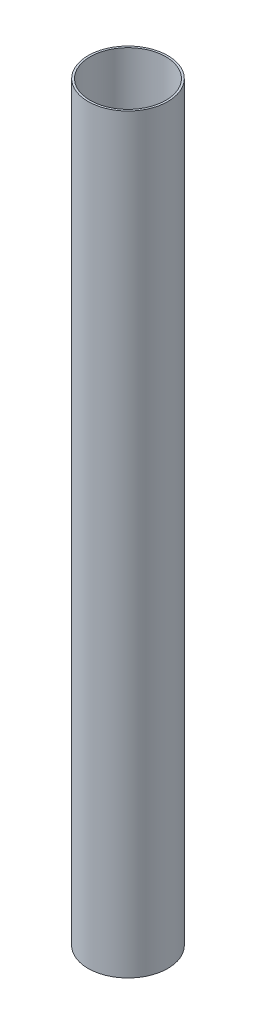
SolidWorks part; units mm, degrees
ref_plane "Front Plane" through (0, 0, 0) normal (0, 0, 1) x (1, 0, 0)
ref_plane "Top Plane" through (0, 0, 0) normal (0, 1, 0) x (1, 0, 0)
ref_plane "Right Plane" through (0, 0, 0) normal (1, 0, 0) x (0, 0, -1)
sketch "Sketch1" plane through (0, 0, 0) normal (0, 1, 0) x (1, 0, 0)
  circle A0 centre (0, 0) radius 32.9
  circle A1 centre (0, 0) radius 31.25
  dimension "D1" = 65.8
  dimension "D2" = 62.5
extrude "Boss-Extrude1" add sketch "Sketch1" along normal blind 620
